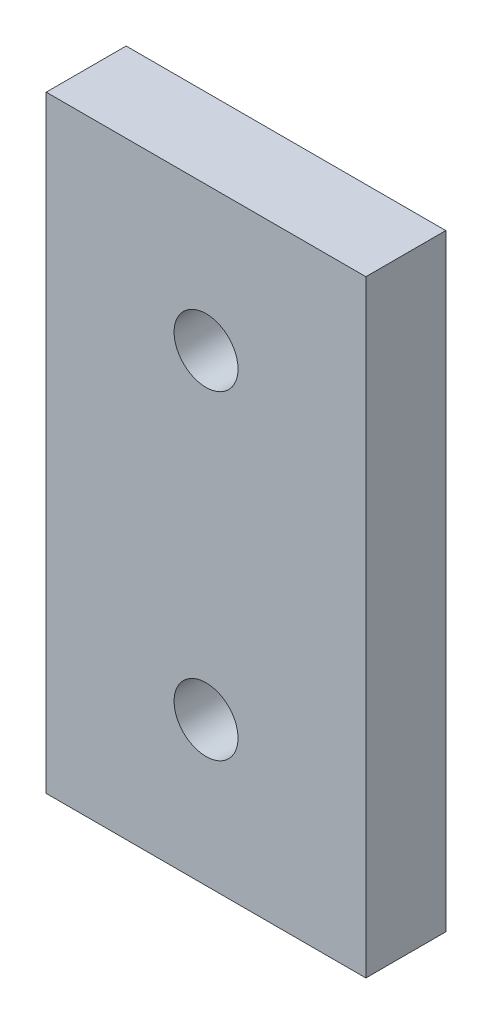
SolidWorks part; units mm, degrees
ref_plane "Front Plane" through (0, 0, 0) normal (0, 0, 1) x (1, 0, 0)
ref_plane "Top Plane" through (0, 0, 0) normal (0, 1, 0) x (1, 0, 0)
ref_plane "Right Plane" through (0, 0, 0) normal (1, 0, 0) x (0, 0, -1)
sketch "Sketch1" plane through (0, 0, 0) normal (0, 0, 1) x (1, 0, 0)
  line L0 (0, 19) -> (0, -19) construction
  line L1 (-10, -19) -> (10, -19)
  line L2 (-10, -19) -> (-10, 19)
  line L3 (-10, 19) -> (10, 19)
  line L4 (10, -19) -> (10, 19)
  line L5 (-10, -19) -> (10, 19) construction
  line L6 (-10, 19) -> (10, -19) construction
  circle A0 centre (0, 10) radius 2
  circle A1 centre (0, -10) radius 2
  point P0 (0, 0)
  dimension "D5" = 4
  dimension "D1" = 20
  dimension "D2" = 38
  dimension "D3" = 20
  dimension "D4" = 10
  dimension "D6" = 9
extrude "Boss-Extrude1" add sketch "Sketch1" along normal blind 5
